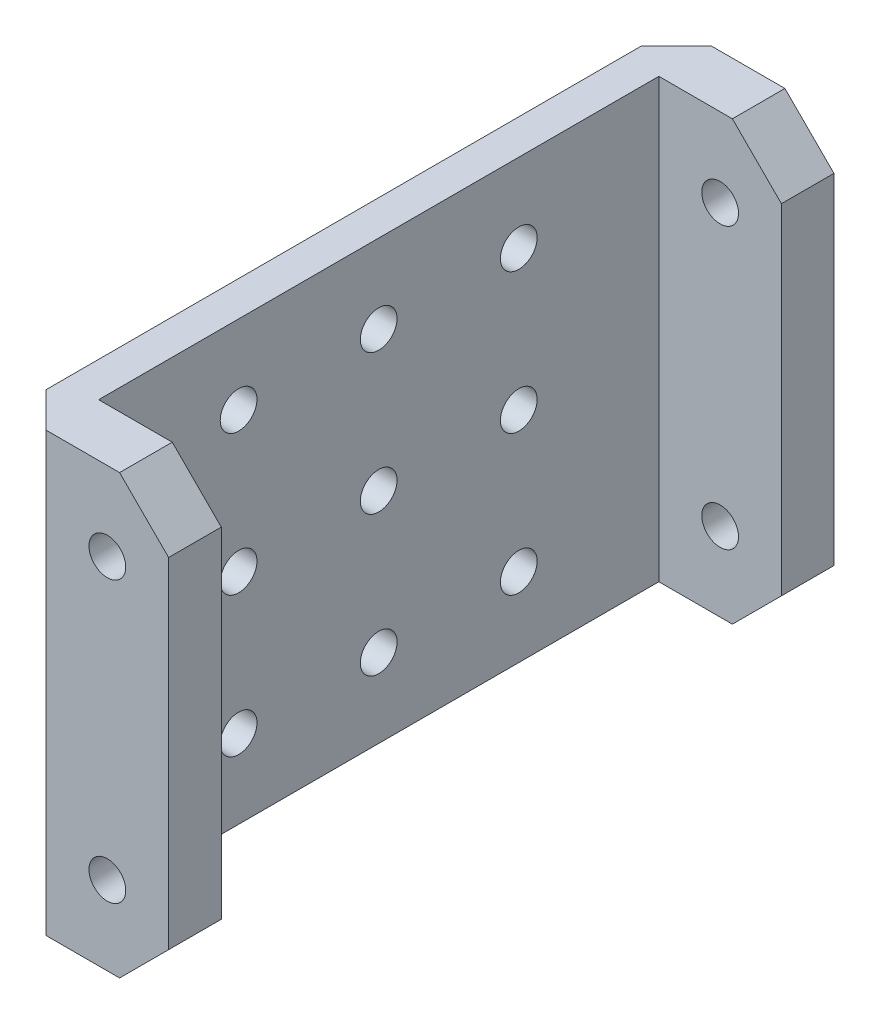
SolidWorks part; units mm, degrees
ref_plane "前视基准面" through (0, 0, 0) normal (0, 0, 1) x (1, 0, 0)
ref_plane "上视基准面" through (0, 0, 0) normal (0, 1, 0) x (1, 0, 0)
ref_plane "右视基准面" through (0, 0, 0) normal (1, 0, 0) x (0, 0, -1)
ref_plane "基准面4" through (0, 0, 0) normal (-1, 0, 0) x (0, -1, 0)
sketch "草图1" plane through (0, 0, 0) normal (-1, 0, 0) x (0, -1, 0)
  line L0 (-25, 38) -> (-25, 0)
  line L1 (-25, 0) -> (0, 0)
  line L2 (0, 0) -> (0, 38)
  line L3 (0, 38) -> (-25, 38)
extrude "凸台-拉伸1" add sketch "草图1" against normal blind 9
sketch "草图2" plane through (0, 25, 0) normal (0, 1, 0) x (-1, 0, 0)
  line L0 (-9, 3) -> (-4, 3)
  line L1 (-4, 3) -> (-3.9965, 5.0803)
  line L2 (-3.9965, 5.0803) -> (-3.9965, 33)
  line L3 (-3.9965, 33) -> (-3.9965, 34.9928)
  line L4 (-3.9965, 34.9928) -> (-9, 34.9928)
  line L5 (-9, 34.9928) -> (-9, 3)
extrude "切除-拉伸1" cut sketch "草图2" against normal through all
hole_wizard "Ø2.1 (2.1) 直径孔1" positions "草图4" profile "草图3" hole size "Ø2.1" standard "ANSI Metric"
sketch "草图4" plane through (0, 0, 0) normal (-1, 0, 0) x (0, 0, 1)
  point P0 (11, 4.5)
sketch "草图3" plane through (0, 4.5, 11) normal (0, 1, 0) x (0, 0, 1)
  line L0 (0, 0) -> (0, 9)
  line L1 (0, 9) -> (1.05, 9)
  line L2 (1.05, 9) -> (1.05, 0)
  line L5 (1.05, 0) -> (0, 0)
  line L11 (0, -6.35) -> (0, 107.95) construction
  dimension "通孔孔直径" = 2.1
  dimension "通孔孔深度" = 9
hole_wizard "Ø2.1 (2.1) 直径孔2" positions "草图6" profile "草图5" hole size "Ø2.1" standard "ANSI Metric"
sketch "草图6" plane through (0, 0, 0) normal (-1, 0, 0) x (0, 0, 1)
  point P0 (19, 4.5)
sketch "草图5" plane through (0, 4.5, 19) normal (0, 1, 0) x (0, 0, 1)
  line L0 (0, 0) -> (0, 9)
  line L1 (0, 9) -> (1.05, 9)
  line L2 (1.05, 9) -> (1.05, 0)
  line L5 (1.05, 0) -> (0, 0)
  line L11 (0, -6.35) -> (0, 107.95) construction
  dimension "通孔孔直径" = 2.1
  dimension "通孔孔深度" = 9
hole_wizard "Ø2.1 (2.1) 直径孔3" positions "草图8" profile "草图7" hole size "Ø2.1" standard "ANSI Metric"
sketch "草图8" plane through (0, 0, 0) normal (-1, 0, 0) x (0, 0, 1)
  point P0 (27, 4.5)
  point P1 (27, 12.5)
  point P2 (27, 20.5)
  point P3 (11, 12.5)
  point P4 (11, 20.5)
  point P5 (19, 20.5)
  point P6 (19, 12.5)
sketch "草图7" plane through (0, 4.5, 27) normal (0, 1, 0) x (0, 0, 1)
  line L0 (0, 0) -> (0, 9)
  line L1 (0, 9) -> (1.05, 9)
  line L2 (1.05, 9) -> (1.05, 0)
  line L5 (1.05, 0) -> (0, 0)
  line L11 (0, -6.35) -> (0, 107.95) construction
  dimension "通孔孔直径" = 2.1
  dimension "通孔孔深度" = 9
hole_wizard "Ø2.1 (2.1) 直径孔4" positions "草图10" profile "草图9" hole size "Ø2.1" standard "ANSI Metric"
sketch "草图10" plane through (0, 0, 34.9928) normal (0, 0, -1) x (-1, 0, 0)
  point P0 (-5.5, 4.5)
  point P1 (-5.5, 20.5)
sketch "草图9" plane through (5.5, 4.5, 34.9928) normal (1, 0, 0) x (0, 1, 0)
  line L0 (0, 0) -> (0, 3.0072)
  line L1 (0, 3.0072) -> (1.05, 3.0072)
  line L2 (1.05, 3.0072) -> (1.05, 0)
  line L5 (1.05, 0) -> (0, 0)
  line L11 (0, -6.35) -> (0, 107.95) construction
  dimension "通孔孔直径" = 2.1
  dimension "通孔孔深度" = 3.0072
chamfer "倒角1" distance 2 angle 45 2 edges at (0, 12.5, 0) (0, 12.5, 38)
sketch "草图12" plane through (0, 0, 3) normal (0, 0, 1) x (1, 0, 0)
  circle A0 centre (5.5, 4.5) radius 1.05
extrude "切除-拉伸2" cut sketch "草图12" against normal blind 10 contours A0
sketch "草图15" plane through (0, 0, 3) normal (0, 0, 1) x (1, 0, 0)
  circle A0 centre (5.5, 20.5) radius 1.05
extrude "切除-拉伸3" cut sketch "草图15" against normal blind 10 contours A0
sketch "草图16" plane through (0, 0, 0) normal (0, -1, 0) x (1, 0, 0)
  line L0 (3.9965, 34.9928) -> (1.9965, 34.9928)
  line L1 (4, 3) -> (2, 3)
  line L2 (2, 3) -> (1.9965, 34.9928)
  line L3 (3.9965, 34.9928) -> (4, 3)
extrude "切除-拉伸4" cut sketch "草图16" against normal through all
sketch "草图17" plane through (0, 0, 38) normal (0, 0, 1) x (1, 0, 0)
  line L0 (9, 22.2) -> (6.2, 25)
  line L5 (6.2, 25) -> (9, 25)
  line L6 (9, 25) -> (9, 22.2)
  line L9 (9, 0) -> (9, 2.8)
  line L10 (6.2, 0) -> (9, 0)
  line L11 (9, 2.8) -> (6.2, 0)
extrude "切除-拉伸5" cut sketch "草图17" against normal through all and the other way through all
